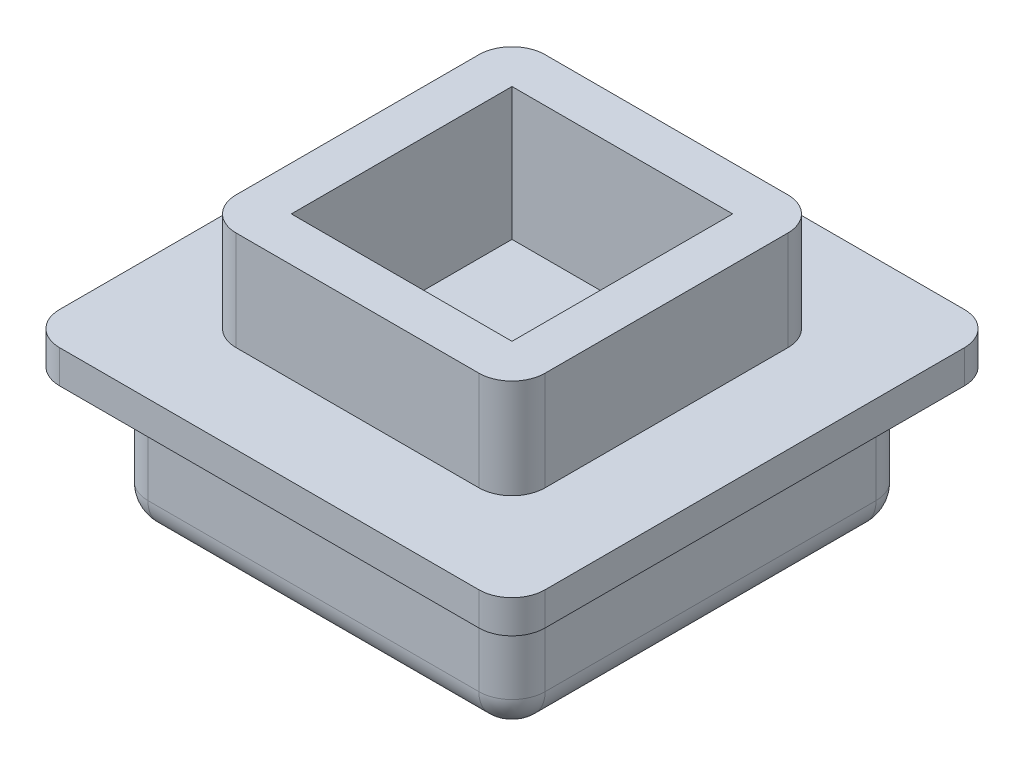
SolidWorks part; units mm, degrees
ref_plane "Front Plane" through (0, 0, 0) normal (0, 0, 1) x (1, 0, 0)
ref_plane "Top Plane" through (0, 0, 0) normal (0, 1, 0) x (1, 0, 0)
ref_plane "Right Plane" through (0, 0, 0) normal (1, 0, 0) x (0, 0, -1)
sketch "Sketch1" plane through (0, 0, 0) normal (0, 1, 0) x (1, 0, 0)
  line L1 (-4.5, -4.5) -> (4.5, -4.5)
  line L2 (-4.5, -4.5) -> (-4.5, 4.5)
  line L3 (-4.5, 4.5) -> (4.5, 4.5)
  line L4 (4.5, -4.5) -> (4.5, 4.5)
  line L5 (-4.5, -4.5) -> (4.5, 4.5) construction
  line L6 (-4.5, 4.5) -> (4.5, -4.5) construction
  point P0 (0, 0)
  dimension "D1" = 9
  dimension "D2" = 9
extrude "Boss-Extrude1" add sketch "Sketch1" along normal blind 3
sketch "Sketch2" plane through (0, 3, 0) normal (0, 1, 0) x (1, 0, 0)
  line L8 (5.5, -5.5) -> (5.5, 5.5)
  line L9 (5.5, 5.5) -> (-5.5, 5.5)
  line L10 (-5.5, 5.5) -> (-5.5, -5.5)
  line L11 (-5.5, -5.5) -> (5.5, -5.5)
  line L12 (5.5, -5.5) -> (5.5, 5.5)
  line L13 (5.5, 5.5) -> (-5.5, 5.5)
  line L14 (-5.5, 5.5) -> (-5.5, -5.5)
  line L15 (-5.5, -5.5) -> (5.5, -5.5)
  dimension "D1" = 1
extrude "Boss-Extrude2" add sketch "Sketch2" along normal blind 0.75
sketch "Sketch3" plane through (0, 3.75, 0) normal (0, 1, 0) x (1, 0, 0)
  line L0 (-3.5, 3.5) -> (3.5, 3.5)
  line L1 (-2.5, -2.5) -> (2.5, -2.5)
  line L2 (-2.5, -2.5) -> (-2.5, 2.5)
  line L3 (-2.5, 2.5) -> (2.5, 2.5)
  line L4 (2.5, -2.5) -> (2.5, 2.5)
  line L5 (-2.5, -2.5) -> (2.5, 2.5) construction
  line L6 (-2.5, 2.5) -> (2.5, -2.5) construction
  line L7 (3.5, -3.5) -> (3.5, 3.5)
  line L8 (-3.5, -3.5) -> (3.5, -3.5)
  line L9 (-3.5, -3.5) -> (-3.5, 3.5)
  point P0 (0, 0)
  dimension "D1" = 5
  dimension "D2" = 5
  dimension "D3" = 1
extrude "Boss-Extrude3" add sketch "Sketch3" along normal blind 2.25
fillet "Fillet1" radius 0.75 12 edges at (-3.5, 4.875, 3.5) (-3.5, 4.875, -3.5) (3.5, 4.875, -3.5) (3.5, 4.875, 3.5) (5.5, 3.375, 5.5) (-5.5, 3.375, 5.5) (-5.5, 3.375, -5.5) (5.5, 3.375, -5.5) (4.5, 1.5, -4.5) (-4.5, 1.5, -4.5) (-4.5, 1.5, 4.5) (4.5, 1.5, 4.5)
fillet "Fillet2" radius 0.75 8 edges at (4.2803, 0, -4.2803) (4.5, 0, 0) (4.2803, 0, 4.2803) (0, 0, 4.5) (-4.2803, 0, 4.2803) (-4.5, 0, 0) (-4.2803, 0, -4.2803) (0, 0, -4.5)
sketch "Sketch4" plane through (0, 3.75, 0) normal (0, 1, 0) x (1, 0, 0)
  line L4 (-2.5, 2.5) -> (-2.5, -2.5)
  line L5 (-2.5, -2.5) -> (2.5, -2.5)
  line L6 (2.5, -2.5) -> (2.5, 2.5)
  line L7 (2.5, 2.5) -> (-2.5, 2.5)
  line L8 (-2.5, 2.5) -> (-2.5, -2.5)
  line L9 (-2.5, -2.5) -> (2.5, -2.5)
  line L10 (2.5, -2.5) -> (2.5, 2.5)
  line L11 (2.5, 2.5) -> (-2.5, 2.5)
  dimension "D1" = 0
extrude "Cut-Extrude1" cut sketch "Sketch4" against normal blind 0.75
